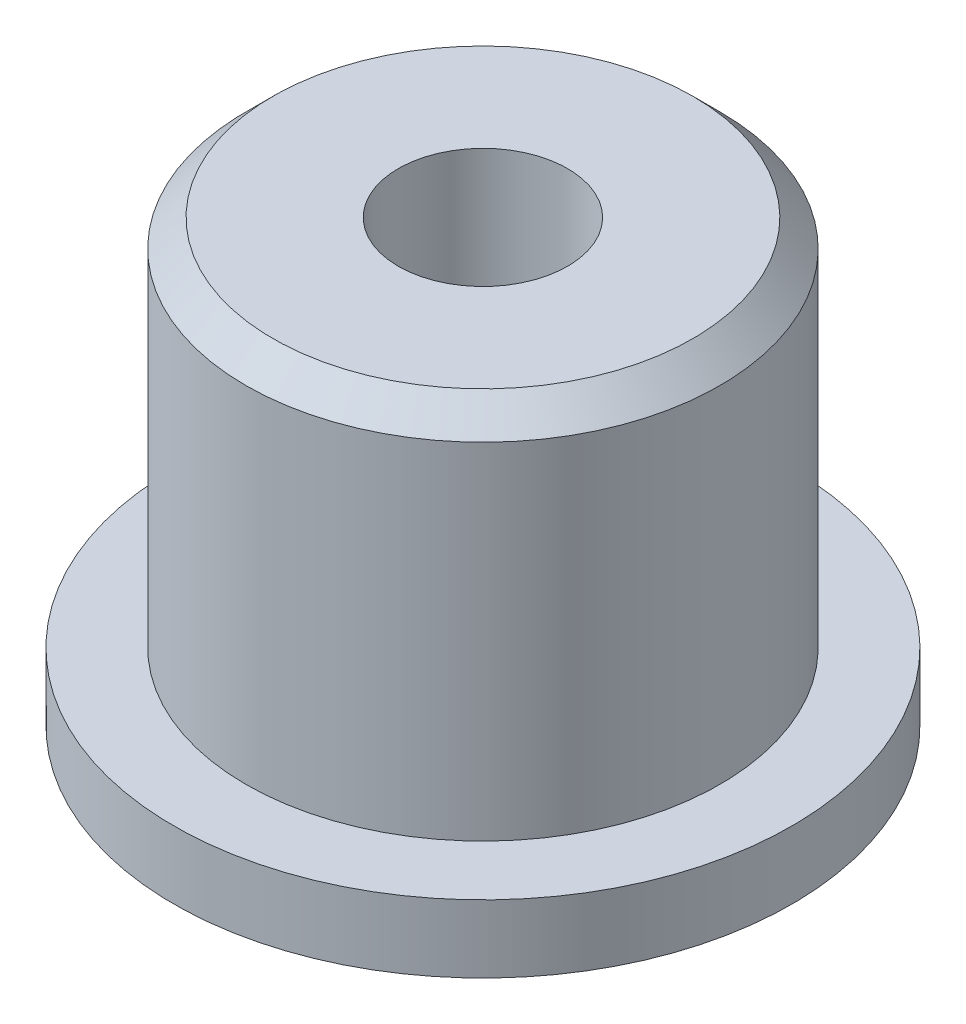
SolidWorks part; units mm, degrees
ref_plane "Front Plane" through (0, 0, 0) normal (0, 0, 1) x (1, 0, 0)
ref_plane "Top Plane" through (0, 0, 0) normal (0, 1, 0) x (1, 0, 0)
ref_plane "Right Plane" through (0, 0, 0) normal (1, 0, 0) x (0, 0, -1)
sketch "Sketch1" plane through (0, 0, 0) normal (0, 1, 0) x (1, 0, 0)
  circle A0 centre (0, 0) radius 18.25
  dimension "D1" = 36.5
extrude "Boss-Extrude1" add sketch "Sketch1" along normal blind 26
sketch "Sketch2" plane through (0, 26, 0) normal (0, 1, 0) x (1, 0, 0)
  circle A0 centre (0, 0) radius 18.25 construction
  circle A1 centre (0, 0) radius 18.25
  circle A2 centre (0, 0) radius 14
  dimension "D1" = 28
extrude "Cut-Extrude1" cut sketch "Sketch2" against normal blind 22
sketch "Sketch3" plane through (0, 26, 0) normal (0, 1, 0) x (1, 0, 0)
  circle A0 centre (0, 0) radius 5
  dimension "D1" = 10
extrude "Cut-Extrude2" cut sketch "Sketch3" against normal through all
sketch "Sketch4" plane through (0, 0, 0) normal (1, 0, 0) x (0, 0, -1)
  line L0 (-14, 24.4) -> (-14, 26)
  line L1 (-14, 26) -> (-14, 4) construction
  line L2 (-14, 26) -> (-12.4, 26)
  line L3 (14, 26) -> (-14, 26) construction
  line L4 (-12.4, 26) -> (-14, 24.4)
  line L5 (0, -1000) -> (0, 49000) construction
  dimension "D1" = 315
  dimension "D2" = 1.6
revolve "Cut-Revolve1" cut sketch "Sketch4" angle 360 about L5
